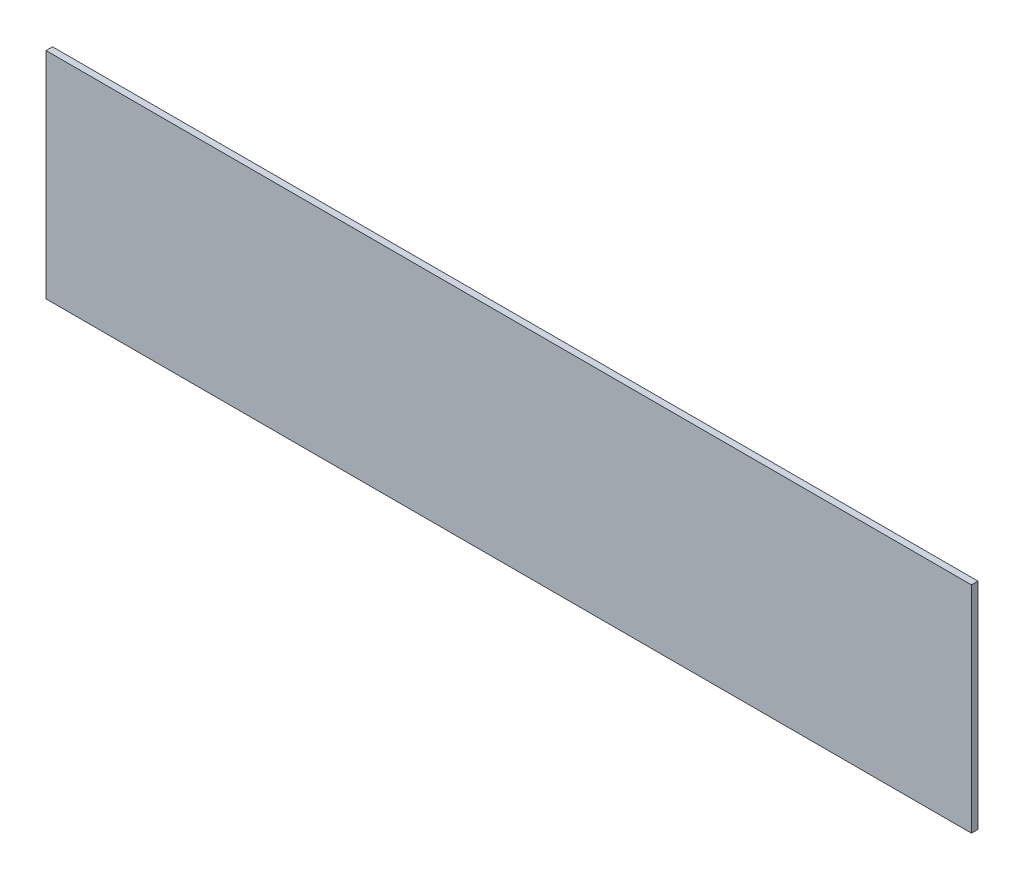
SolidWorks part; units mm, degrees
ref_plane "前视基准面" through (0, 0, 0) normal (0, 0, 1) x (1, 0, 0)
ref_plane "上视基准面" through (0, 0, 0) normal (0, 1, 0) x (1, 0, 0)
ref_plane "右视基准面" through (0, 0, 0) normal (1, 0, 0) x (0, 0, -1)
sketch "草图1" plane through (0, 0, 0) normal (0, 0, 1) x (1, 0, 0)
  line L1 (-66.8615, 1.6534) -> (75.1385, 1.6534)
  line L2 (-66.8615, 1.6534) -> (-66.8615, -31.3466)
  line L3 (-66.8615, -31.3466) -> (75.1385, -31.3466)
  line L4 (75.1385, 1.6534) -> (75.1385, -31.3466)
  dimension "D1" = 142
  dimension "D2" = 33
extrude "凸台-拉伸1" add sketch "草图1" along normal blind 1
